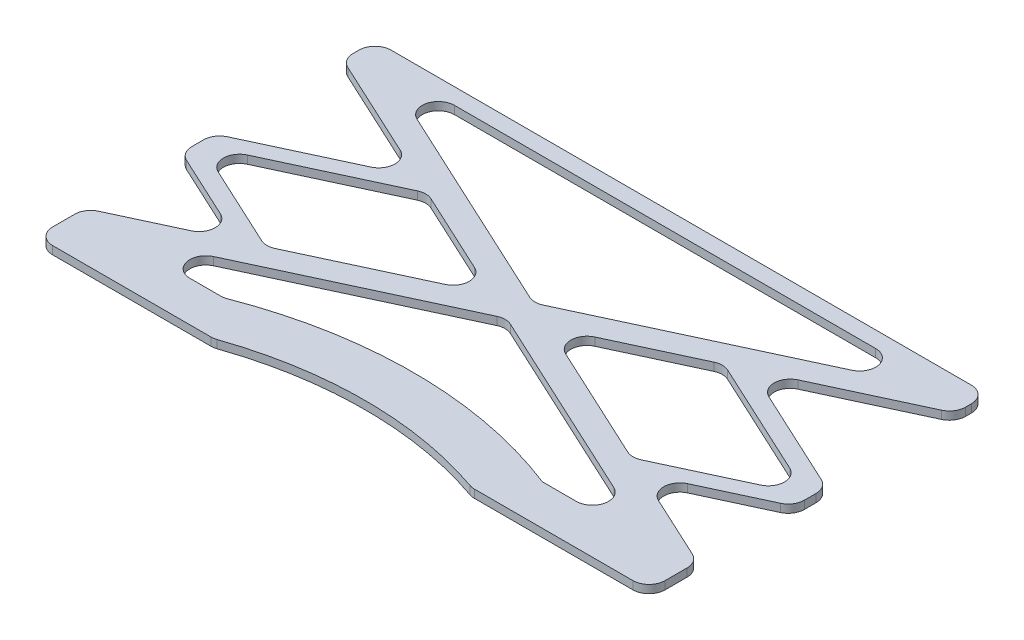
SolidWorks part; units mm, degrees
material "6061 Alloy"
ref_plane "Front Plane" through (0, 0, 0) normal (0, 0, 1) x (1, 0, 0)
ref_plane "Top Plane" through (0, 0, 0) normal (0, 1, 0) x (1, 0, 0)
ref_plane "Right Plane" through (0, 0, 0) normal (1, 0, 0) x (0, 0, -1)
sketch "Sketch1" plane through (0, 0, 0) normal (0, 1, 0) x (1, 0, 0)
  line L0 (-120.65, 0) -> (120.65, 0)
  line L1 (-120.65, 0) -> (-120.65, -12.7)
  line L4 (-120.65, -114.3) -> (-120.65, -133.35)
  line L5 (-120.65, -133.35) -> (-50.8, -133.35)
  line L6 (120.65, 0) -> (120.65, -12.7)
  line L7 (120.65, -12.7) -> (65.9768, -38.1)
  line L9 (120.65, -114.3) -> (120.65, -133.35)
  line L10 (120.65, -133.35) -> (50.8, -133.35)
  line L11 (65.9768, -38.1) -> (120.65, -63.5)
  line L12 (120.65, -63.5) -> (120.65, -76.2)
  line L13 (120.65, -76.2) -> (79.6451, -95.25)
  line L17 (79.6451, -95.25) -> (120.65, -114.3)
  line L18 (-120.65, -12.7) -> (-65.9768, -38.1)
  line L19 (-65.9768, -38.1) -> (-120.65, -63.5)
  line L20 (-120.65, -63.5) -> (-120.65, -76.2)
  line L21 (-120.65, -76.2) -> (-79.6451, -95.25)
  line L22 (-79.6451, -95.25) -> (-120.65, -114.3)
  line L23 (-111.7113, -6.35) -> (111.7113, -6.35)
  line L24 (111.7113, -6.35) -> (0, -58.2486)
  line L25 (0, -58.2486) -> (-111.7113, -6.35)
  line L26 (-58.4411, -41.6009) -> (-119.247, -69.85)
  line L27 (-119.247, -69.85) -> (-72.1094, -91.7491)
  line L28 (-72.1094, -91.7491) -> (-11.3035, -63.5)
  line L29 (-11.3035, -63.5) -> (-58.4411, -41.6009)
  line L30 (11.3035, -63.5) -> (58.4411, -41.6009)
  line L31 (58.4411, -41.6009) -> (119.247, -69.85)
  line L32 (119.247, -69.85) -> (72.1094, -91.7491)
  line L33 (72.1094, -91.7491) -> (11.3035, -63.5)
  line L35 (-104.8771, -117.475) -> (0, -68.7514)
  line L36 (0, -68.7514) -> (104.8771, -117.475)
  line L37 (104.8771, -117.475) -> (62.7375, -117.475)
  line L38 (-104.8771, -117.475) -> (-62.7375, -117.475)
  arc A1 (-50.8, -133.35) -> (50.8, -133.35) centre (0, -277.0341) cw
  arc A2 (-62.7375, -117.475) -> (62.7375, -117.475) centre (0, -277.0341) cw
  point P4 (0, 0)
  point P5 (58.091, -104.775)
  point P36 (0, -6.35)
  point P37 (0, 0)
  point P40 (-93.8706, -101.6)
  point P41 (-104.783, -106.9542)
  point P42 (0, -68.1313)
  point P43 (-93.0311, -104.775)
  dimension "D1" = 241.3
  dimension "D5" = 9.525
  dimension "D14" = 15.875
  dimension "D15" = 19.05
  dimension "D17" = 152.4
  dimension "D2" = 12.7
  dimension "D3" = 12.7
  dimension "D4" = 19.05
  dimension "D6" = 63.5
  dimension "D7" = 50.8
  dimension "D8" = 6.35
  dimension "D9" = 6.35
  dimension "D10" = 9.525
  dimension "D11" = 9.525
  dimension "D12" = 6.35
  dimension "D13" = 6.35
  dimension "D16" = 9.525
  dimension "D18" = 101.6
extrude "Boss-Extrude1" add sketch "Sketch1" along normal blind 3.175
fillet "Fillet1" radius 6.35 15 edges at (0, 1.5875, 58.2486) (-111.7113, 1.5875, 6.35) (111.7113, 1.5875, 6.35) (104.8771, 1.5875, 117.475) (0, 1.5875, 68.7514) (-104.8771, 1.5875, 117.475) (-62.7375, 1.5875, 117.475) (72.1094, 1.5875, 91.7491) (119.247, 1.5875, 69.85) (58.4411, 1.5875, 41.6009) (11.3035, 1.5875, 63.5) (-11.3035, 1.5875, 63.5) (-72.1094, 1.5875, 91.7491) (-119.247, 1.5875, 69.85) (-58.4411, 1.5875, 41.6009)
fillet "Fillet2" radius 6.35 18 edges at (120.65, 1.5875, 0) (120.65, 1.5875, 12.7) (65.9768, 1.5875, 38.1) (120.65, 1.5875, 63.5) (120.65, 1.5875, 76.2) (120.65, 1.5875, 114.3) (79.6451, 1.5875, 95.25) (120.65, 1.5875, 133.35) (50.8, 1.5875, 133.35) (-50.8, 1.5875, 133.35) (-120.65, 1.5875, 114.3) (-120.65, 1.5875, 133.35) (-120.65, 1.5875, 0) (-120.65, 1.5875, 12.7) (-65.9768, 1.5875, 38.1) (-120.65, 1.5875, 63.5) (-120.65, 1.5875, 76.2) (-79.6451, 1.5875, 95.25)
